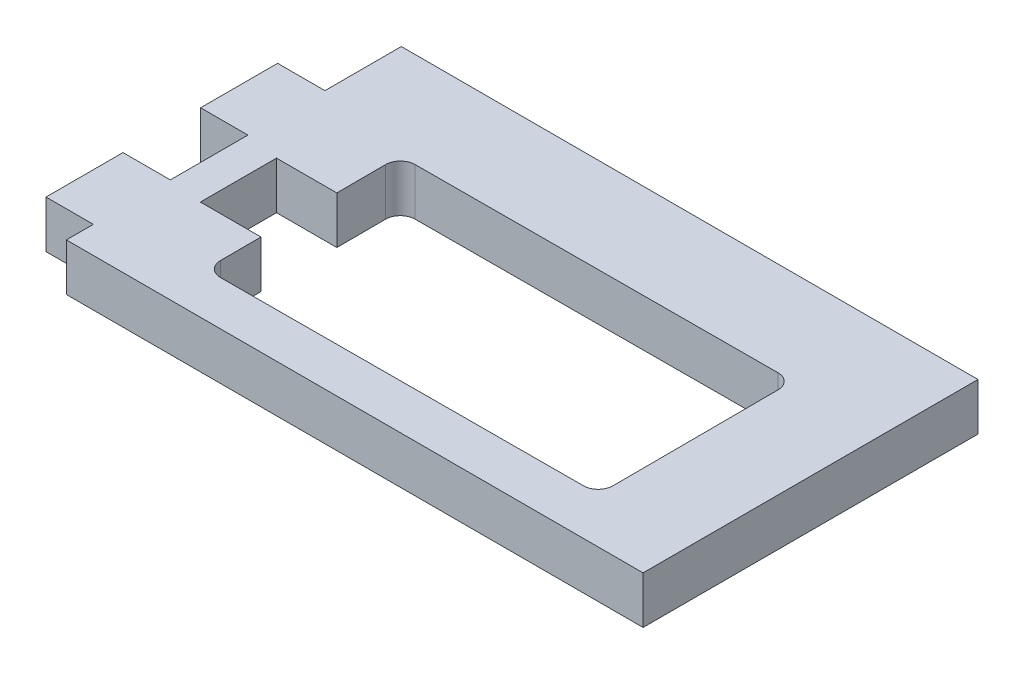
SolidWorks part; units mm, degrees
ref_plane "Front Plane" through (0, 0, 0) normal (0, 0, 1) x (1, 0, 0)
ref_plane "Top Plane" through (0, 0, 0) normal (0, 1, 0) x (1, 0, 0)
ref_plane "Right Plane" through (0, 0, 0) normal (1, 0, 0) x (0, 0, -1)
sketch "Sketch1" plane through (0, 0, 0) normal (0, 1, 0) x (1, 0, 0)
  line L1 (0, 0) -> (127, 0)
  line L2 (0, 0) -> (0, 101.6)
  line L3 (0, 101.6) -> (127, 101.6)
  line L4 (127, 0) -> (127, 101.6)
  line L5 (0, 0) -> (127, 101.6) construction
  line L6 (0, 101.6) -> (127, 0) construction
  point P4 (63.5, 50.8)
extrude "Boss-Extrude1" add sketch "Sketch1" along normal blind 4.8
sketch "Sketch3" plane through (0, 4.8, 0) normal (0, 1, 0) x (1, 0, 0)
  line L4 (0, 101.6) -> (0, 0)
  line L5 (0, 0) -> (127, 0)
  line L6 (127, 0) -> (127, 101.6)
  line L7 (127, 101.6) -> (0, 101.6)
  line L8 (0, 101.6) -> (0, 0)
  line L9 (0, 0) -> (127, 0)
  line L10 (127, 0) -> (127, 101.6)
  line L11 (127, 101.6) -> (0, 101.6)
  line L16 (61.8909, 65.23) -> (98.8212, 65.3483)
  line L17 (98.7064, 65.2327) -> (62.0065, 65.1151)
  line L18 (60.4503, 46.6948) -> (60.3958, 63.7252)
  line L19 (60.5113, 63.6104) -> (60.5652, 46.8104)
  line L20 (98.8854, 45.318) -> (61.9551, 45.1997)
  line L21 (62.0699, 45.3152) -> (98.7698, 45.4328)
  line L22 (100.326, 63.8531) -> (100.3805, 46.8228)
  line L23 (100.265, 46.9376) -> (100.2111, 63.7376)
  arc A4 (100.2111, 63.7376) -> (98.7064, 65.2327) centre (98.7112, 63.7328) ccw
  arc A5 (62.0065, 65.1151) -> (60.5113, 63.6104) centre (62.0113, 63.6152) ccw
  arc A6 (60.5652, 46.8104) -> (62.0699, 45.3152) centre (62.0651, 46.8152) ccw
  arc A7 (98.7698, 45.4328) -> (100.265, 46.9376) centre (98.765, 46.9328) ccw
  ellipse E4 centre (98.8259, 63.8483) end of major axis (97.7686, 62.7841) minor radius 1.5 (100.326, 63.8531) -> (98.8212, 65.3483) ccw
  ellipse E5 centre (61.8958, 63.7299) end of major axis (62.9599, 62.6726) minor radius 1.5 (61.8909, 65.23) -> (60.3958, 63.7252) ccw
  ellipse E6 centre (61.9504, 46.6997) end of major axis (63.0077, 47.7638) minor radius 1.5 (60.4503, 46.6948) -> (61.9551, 45.1997) ccw
  ellipse E7 centre (98.8805, 46.818) end of major axis (97.8164, 47.8753) minor radius 1.5 (98.8854, 45.318) -> (100.3805, 46.8228) ccw
  dimension "D1" = 0
extrude "Cut-Extrude1" cut sketch "Sketch3" against normal through all contours L21 A7 L23 A4 L17 A5 L19 A6
sketch "Sketch4" plane through (0, 0, 0) normal (0, -1, 0) x (1, 0, 0)
  line L6 (46.1381, -35.7265) -> (109.4407, -35.7265)
  line L8 (46.1381, -35.7265) -> (46.1381, -74.7851)
  line L9 (46.1381, -74.7851) -> (109.4407, -74.7851)
  line L10 (109.4407, -35.7265) -> (109.4407, -74.7851)
  line L11 (46.1381, -35.7265) -> (109.4407, -74.7851) construction
  line L12 (46.1381, -74.7851) -> (109.4407, -35.7265) construction
  line L16 (60.5381, -55.2558) -> (46.1381, -55.2558) construction
  line L18 (60.5113, -63.6104) -> (60.5652, -46.8104) construction
  line L19 (65.5692, -45.3265) -> (65.5692, -35.7265) construction
  line L20 (62.0699, -45.3152) -> (98.7698, -45.4328) construction
  line L21 (67.5977, -65.1331) -> (67.5977, -74.7851)
  line L22 (98.7064, -65.2327) -> (62.0065, -65.1151) construction
  point P4 (77.7894, -55.2558)
  line M13 (0, 0) -> (0, -101.6)
  line M14 (0, -101.6) -> (127, -101.6)
  line M15 (127, -101.6) -> (127, 0)
  line M16 (127, 0) -> (0, 0)
  dimension "D2" = 9.6
  dimension "D3" = 9.652
  dimension "D4" = 39.0586
  dimension "D1" = 14.4
  dimension "D5" = 63.3026
extrude "Cut-Extrude3" cut sketch "Sketch4" against normal through all contours L6 L10 L9 L8 M16 M13 M14 M15
sketch "Sketch5" plane through (0, 0, 0) normal (0, -1, 0) x (1, 0, 0)
  line L6 (50.9381, -35.7265) -> (46.1381, -35.7265)
  line L7 (50.9381, -35.7265) -> (50.9381, -43.5382)
  line L8 (50.9381, -43.5382) -> (46.1381, -43.5382)
  line L9 (46.1381, -35.7265) -> (46.1381, -43.5382)
  line L10 (50.9381, -35.7265) -> (46.1381, -43.5382) construction
  line L11 (50.9381, -43.5382) -> (46.1381, -35.7265) construction
  line L12 (50.9381, -51.3499) -> (46.1381, -51.3499)
  line L13 (50.9381, -51.3499) -> (50.9381, -59.2239)
  line L14 (50.9381, -59.2239) -> (46.1381, -59.2239)
  line L15 (46.1381, -51.3499) -> (46.1381, -59.2239)
  line L16 (50.9381, -51.3499) -> (46.1381, -59.2239) construction
  line L17 (50.9381, -59.2239) -> (46.1381, -51.3499) construction
  line L18 (50.9381, -67.0356) -> (46.1381, -67.0356)
  line L19 (50.9381, -67.0356) -> (50.9381, -74.7851)
  line L20 (50.9381, -74.7851) -> (46.1381, -74.7851)
  line L21 (46.1381, -67.0356) -> (46.1381, -74.7851)
  line L22 (50.9381, -67.0356) -> (46.1381, -74.7851) construction
  line L23 (50.9381, -74.7851) -> (46.1381, -67.0356) construction
  line L24 (46.1381, -35.7265) -> (46.1381, -74.7851) construction
  line L26 (46.1381, -43.5382) -> (46.1381, -51.3499) construction
  line L27 (46.1381, -59.2239) -> (46.1381, -67.0356) construction
  point P4 (48.5381, -39.6323)
  point P9 (48.5381, -55.2869)
  point P14 (48.5381, -70.9103)
  dimension "D1" = 7.8117
  dimension "D2" = 7.8117
  dimension "D3" = 7.874
  dimension "D4" = 4.8
extrude "Cut-Extrude4" cut sketch "Sketch5" against normal through all
sketch "Sketch6" plane through (0, 0, 0) normal (0, -1, 0) x (1, 0, 0)
  line L0 (60.5113, -63.6104) -> (60.5652, -46.8104) construction
  line L1 (60.552, -50.9288) -> (54.4093, -50.9288)
  line L2 (60.552, -50.9288) -> (60.552, -58.6515)
  line L3 (60.552, -58.6515) -> (54.4093, -58.6515)
  line L4 (54.4093, -50.9288) -> (54.4093, -58.6515)
  line L5 (60.552, -50.9288) -> (54.4093, -58.6515) construction
  line L6 (60.552, -58.6515) -> (54.4093, -50.9288) construction
  point P4 (57.4807, -54.7902)
extrude "Cut-Extrude5" cut sketch "Sketch6" against normal through all
sketch "Sketch7" plane through (0, 4.8, 0) normal (0, 1, 0) x (1, 0, 0)
  line L0 (109.4407, 35.7265) -> (109.4407, 74.7851) construction
  line L1 (109.4407, 40.8065) -> (50.9381, 40.8065)
  line L2 (109.4407, 40.8065) -> (109.4407, 35.7265)
  line L3 (109.4407, 35.7265) -> (50.9381, 35.7265)
  line L4 (50.9381, 40.8065) -> (50.9381, 35.7265)
  point P7 (50.9381, 38.2665)
  dimension "D1" = 2.54
extrude "Cut-Extrude6" cut sketch "Sketch7" against normal through all
equation "\"MDF\"= 4.8mm"
equation "\"Foamcore\"= 4.6mm"
equation "\"PCB\" = 1.6mm"
equation "\"GMaterial\"= \"MDF\""
equation "\"BaseWidth\" = 10in"
equation "\"SkidLength\" = 1in"
equation "\"SkidClearance\" = 0.4in"
equation "\"MotorMountLength\" = 2in"
equation "\"MotorMountWidth\" = \"GMaterial\""
equation "\"MotorMountHeight\" = 2.25in"
equation "\"UnoStackWidth\" = 77.4mm"
equation "\"UnoStackLength\" = 79.8mm"
equation "\"UnoStackHeight\" = 34.2mm"
equation "\"TallHexRiserHeight\" = 22.2mm"
equation "\"PingPongBallSize\" = 40mm"
equation "\"BarrelLength\" = 9in"
equation "\"BarrelSize\" = \"PingPongBallSize\""
equation "\"PlatformLength\" = 4in"
equation "\"PlatformWidth\" = 6in"
equation "\"WheelWidth\"= 26mm"
equation "\"WheelDiameter\"=2.99213"
equation "\"D1@Boss-Extrude1\"=\"MDF\""
equation "\"D2@Sketch4\"=\"MDF\"*2"
equation "\"ServoMountLength\"= 1.53774"
equation "\"D4@Sketch4\"=\"ServoMountLength\""
equation "\"D1@Sketch5\"=\"ServoMountLength\"/5"
equation "\"D2@Sketch5\"=\"ServoMountLength\"/5"
equation "\"D1@Sketch4\"=\"MDF\"*3"
equation "\"D4@Sketch5\"=\"GMaterial\""
equation "\"ServoMountHeight\"=2.49223"
